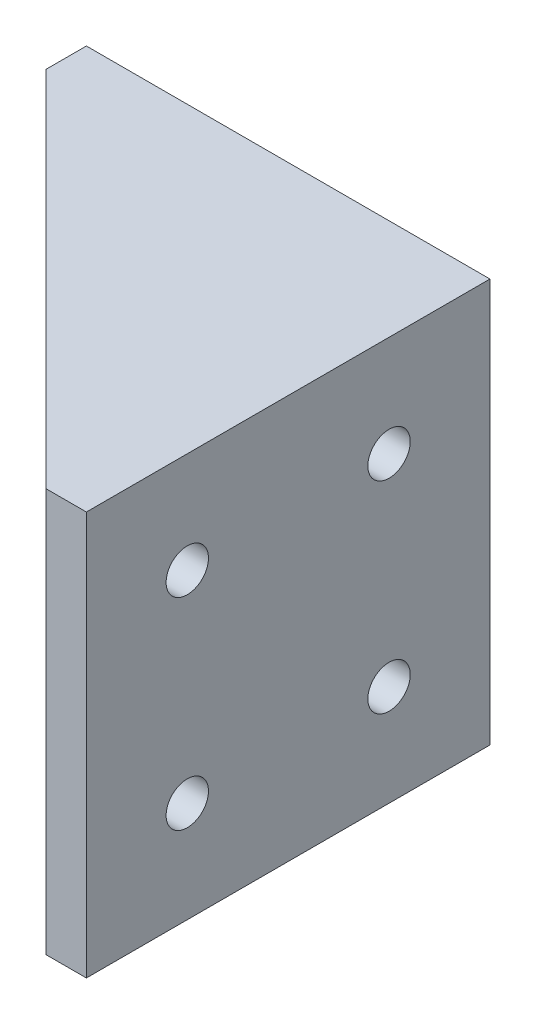
SolidWorks part; units mm, degrees
ref_plane "Front Plane" through (0, 0, 0) normal (0, 0, 1) x (1, 0, 0)
ref_plane "Top Plane" through (0, 0, 0) normal (0, 1, 0) x (1, 0, 0)
ref_plane "Right Plane" through (0, 0, 0) normal (1, 0, 0) x (0, 0, -1)
sketch "Sketch1" plane through (0, 0, 0) normal (0, 1, 0) x (1, 0, 0)
  line L0 (0, 0) -> (0, 40)
  line L1 (0, 40) -> (-40, 40)
  line L2 (-40, 40) -> (-40, 36)
  line L3 (0, 0) -> (-4, 0)
  line L4 (-4, 0) -> (-4, 36)
  line L5 (-4, 36) -> (-40, 36)
extrude "Boss-Extrude1" add sketch "Sketch1" along normal blind 40
sketch "Sketch2" plane through (0, 0, -40) normal (0, 0, -1) x (-1, 0, 0)
  circle A0 centre (30, 30) radius 2.1
  circle A1 centre (30, 10) radius 2.1
  circle A2 centre (10, 10) radius 2.1
  circle A3 centre (10, 30) radius 2.1
extrude "Cut-Extrude1" cut sketch "Sketch2" against normal blind 40
sketch "Sketch3" plane through (0, 0, 0) normal (1, 0, 0) x (0, 0, -1)
  circle A0 centre (10, 30) radius 2.1
  circle A1 centre (30, 30) radius 2.1
  circle A2 centre (30, 10) radius 2.1
  circle A3 centre (10, 10) radius 2.1
extrude "Cut-Extrude2" cut sketch "Sketch3" against normal blind 40
sketch "Sketch4" plane through (0, 40, 0) normal (0, 1, 0) x (1, 0, 0)
  line L0 (-40, 36) -> (-4, 0)
  line L1 (-4, 0) -> (-4, 36)
  line L2 (-4, 36) -> (-4, 0) construction
  line L3 (-40, 36) -> (-4, 36) construction
  line L4 (-4, 36) -> (-40, 36)
extrude "Boss-Extrude2" add sketch "Sketch4" against normal blind 4
sketch "Sketch5" plane through (0, 0, 0) normal (0, -1, 0) x (1, 0, 0)
  line L0 (-4, -36) -> (-4, 0)
  line L1 (-40, -36) -> (-4, 0) construction
  line L2 (-4, 0) -> (-4, -36) construction
  line L3 (-4, 0) -> (-40, -36)
  line L4 (-40, -36) -> (-4, -36)
extrude "Boss-Extrude3" add sketch "Sketch5" against normal blind 4
